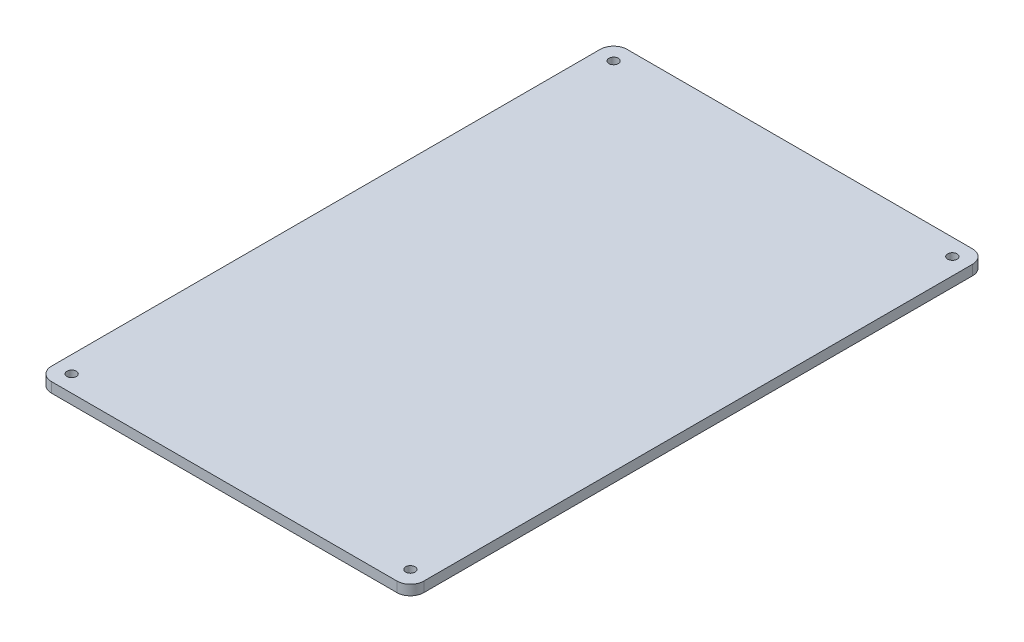
SolidWorks part; units mm, degrees
ref_plane "Front Plane" through (0, 0, 0) normal (0, 0, 1) x (1, 0, 0)
ref_plane "Top Plane" through (0, 0, 0) normal (0, 1, 0) x (1, 0, 0)
ref_plane "Right Plane" through (0, 0, 0) normal (1, 0, 0) x (0, 0, -1)
sketch "Sketch1" plane through (0, 0, 0) normal (0, 1, 0) x (1, 0, 0)
  line L0 (-55.5, 80.579) -> (-55.5, -83.0178)
  line L1 (-51.5, -87.0178) -> (51.5, -87.0178)
  line L2 (55.5, -83.0178) -> (55.5, 80.579)
  line L3 (51.5, 84.579) -> (-51.5, 84.579)
  line L4 (-57.5, 86.579) -> (-57.5, -89.0178)
  line L5 (-57.5, -89.0178) -> (57.5, -89.0178)
  line L6 (57.5, -89.0178) -> (57.5, 86.579)
  line L7 (57.5, 86.579) -> (-57.5, 86.579)
  circle A0 centre (-50.5, -82.0178) radius 1.4
  circle A1 centre (50.5, -82.0178) radius 1.4
  circle A2 centre (50.5, 79.579) radius 1.4
  circle A3 centre (-50.5, 79.579) radius 1.4
  arc A4 (51.5, -87.0178) -> (55.5, -83.0178) centre (51.5, -83.0178) ccw
  arc A5 (-55.5, -83.0178) -> (-51.5, -87.0178) centre (-51.5, -83.0178) ccw
  arc A6 (55.5, 80.579) -> (51.5, 84.579) centre (51.5, 80.579) ccw
  arc A7 (-55.5, 80.579) -> (-51.5, 84.579) centre (-51.5, 80.579) cw
  dimension "D1" = 4
extrude "Boss-Extrude1" add sketch "Sketch1" along normal blind 3 contours A7 L0 A5 L1 A4 L2 A6 L3 A3 A2 A1 A0
